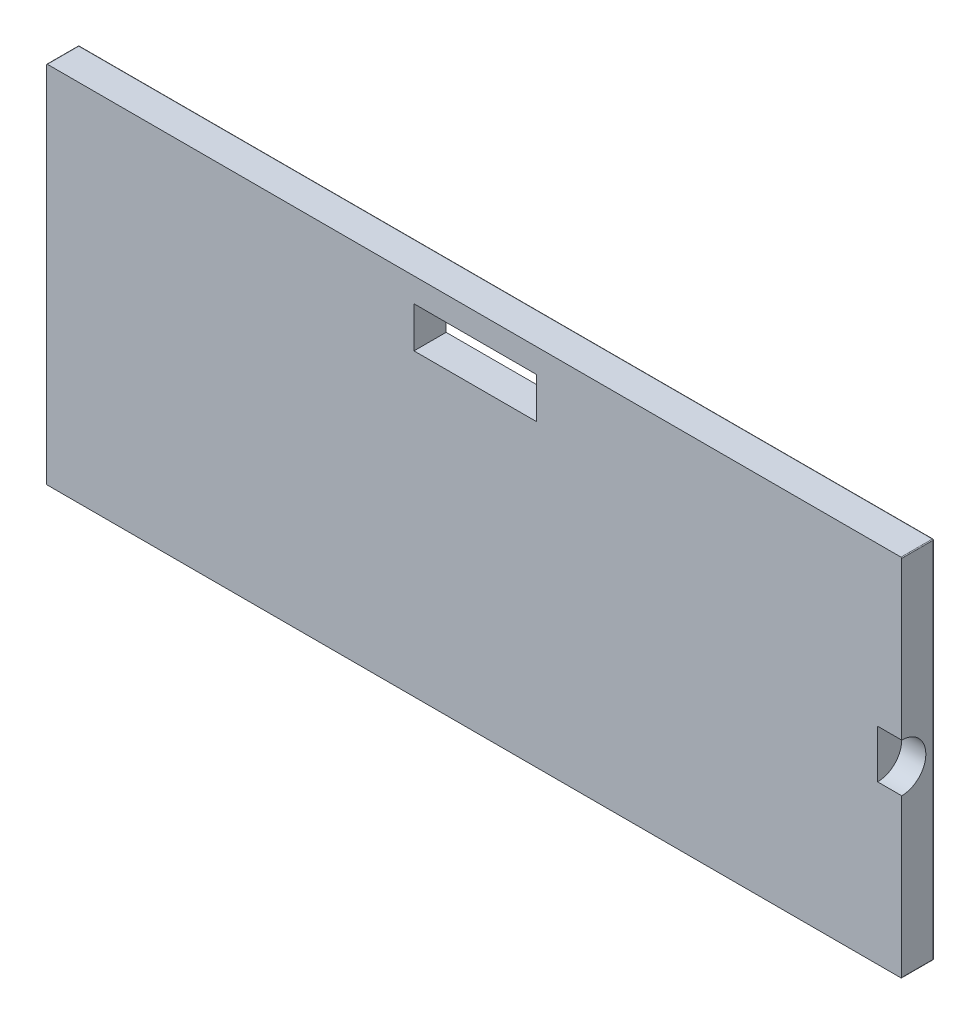
SolidWorks part; units mm, degrees
ref_plane "Front Plane" through (0, 0, 0) normal (0, 0, 1) x (1, 0, 0)
ref_plane "Top Plane" through (0, 0, 0) normal (0, 1, 0) x (1, 0, 0)
ref_plane "Right Plane" through (0, 0, 0) normal (1, 0, 0) x (0, 0, -1)
sketch "Sketch1" plane through (0, 0, 0) normal (0, 0, 1) x (1, 0, 0)
  line L1 (0, 0) -> (2704.084, 0)
  line L2 (0, 0) -> (0, 1152.398)
  line L3 (0, 1152.398) -> (2704.084, 1152.398)
  line L4 (2704.084, 0) -> (2704.084, 1152.398)
  line L5 (1161.796, 1076.198) -> (1548.892, 1076.198)
  line L6 (1161.796, 1076.198) -> (1161.796, 947.166)
  line L7 (1161.796, 947.166) -> (1548.892, 947.166)
  line L8 (1548.892, 1076.198) -> (1548.892, 947.166)
  dimension "D1" = 2704.084
  dimension "D2" = 1152.398
  dimension "D3" = 387.096
  dimension "D4" = 1161.796
  dimension "D5" = 129.032
  dimension "D6" = 76.2
extrude "Boss-Extrude1" add sketch "Sketch1" along normal blind 76.2 and the other way blind 25.4
sketch "Sketch2" plane through (2704.084, 0, 0) normal (1, 0, 0) x (0, 0, -1)
  line L0 (-76.2, 0) -> (-76.2, 1152.398) construction
  circle A0 centre (-76.2, 576.199) radius 76.2
extrude "Cut-Extrude1" cut sketch "Sketch2" against normal blind 76.2
fillet "Fillet1" radius 2.54 8 edges at (1352.042, 0, -25.4) (2704.084, 576.199, -25.4) (1352.042, 1152.398, -25.4) (0, 576.199, -25.4) (0, 1152.398, 25.4) (0, 0, 25.4) (2704.084, 0, 25.4) (2704.084, 1152.398, 25.4)
